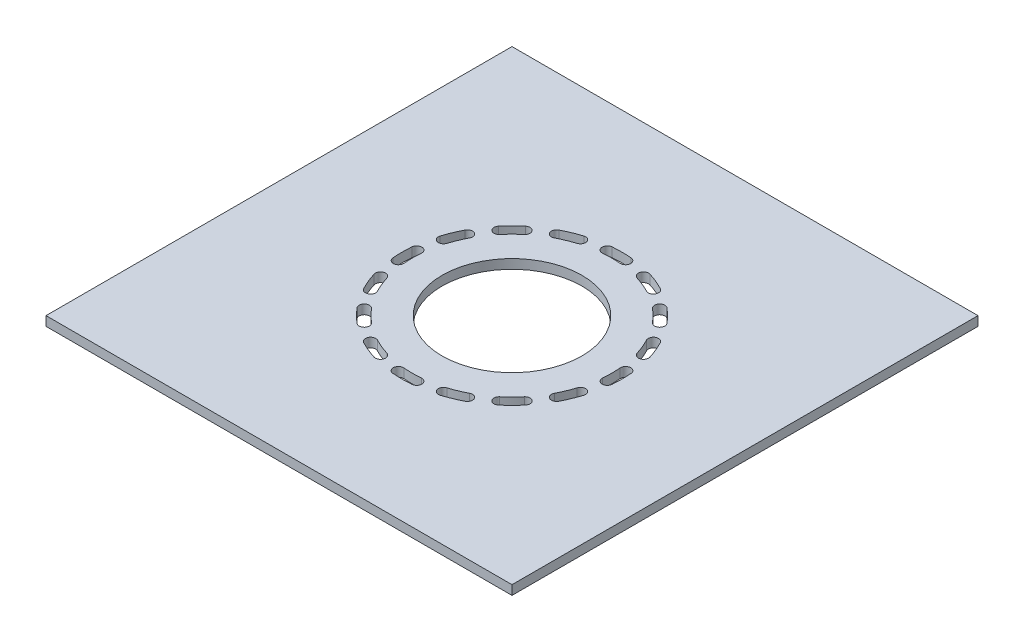
SolidWorks part; units mm, degrees
ref_plane "前视基准面" through (0, 0, 0) normal (0, 0, 1) x (1, 0, 0)
ref_plane "上视基准面" through (0, 0, 0) normal (0, 1, 0) x (1, 0, 0)
ref_plane "右视基准面" through (0, 0, 0) normal (1, 0, 0) x (0, 0, -1)
sketch "草图1" plane through (0, 0, 0) normal (0, 1, 0) x (1, 0, 0)
  line L0 (15.1321, 15.1321) -> (16.6877, 16.6877) construction
  line L1 (-50, -50) -> (50, -50)
  line L2 (-50, -50) -> (-50, 50)
  line L3 (-50, 50) -> (50, 50)
  line L4 (50, -50) -> (50, 50)
  line L5 (-50, -50) -> (50, 50) construction
  line L6 (-50, 50) -> (50, -50) construction
  line L7 (15.1698, 18.0786) -> (0, 0) construction
  circle A0 centre (0, 0) radius 15
  circle A1 centre (0, 0) radius 22.5 construction
  arc A2 (16.3934, 13.7557) -> (13.7557, 16.3934) centre (0, 0) ccw
  arc A3 (18.0786, 15.1698) -> (15.1698, 18.0786) centre (0, 0) ccw
  arc A4 (15.1698, 18.0786) -> (13.7557, 16.3934) centre (14.4627, 17.236) ccw
  arc A5 (18.0786, 15.1698) -> (16.3934, 13.7557) centre (17.236, 14.4627) cw
  arc A6 (20.9335, 10.8973) -> (18.982, 9.8814) centre (19.9577, 10.3893) ccw
  arc A7 (22.5077, 7.0967) -> (20.9335, 10.8973) centre (0, 0) ccw
  arc A8 (20.4095, 6.4351) -> (18.982, 9.8814) centre (0, 0) ccw
  arc A9 (22.5077, 7.0967) -> (20.4095, 6.4351) centre (21.4586, 6.7659) cw
  arc A10 (23.5102, 2.0569) -> (21.3186, 1.8651) centre (22.4144, 1.961) ccw
  arc A11 (23.5102, -2.0569) -> (23.5102, 2.0569) centre (0, 0) ccw
  arc A12 (21.3186, -1.8651) -> (21.3186, 1.8651) centre (0, 0) ccw
  arc A13 (23.5102, -2.0569) -> (21.3186, -1.8651) centre (22.4144, -1.961) cw
  arc A14 (22.5077, -7.0967) -> (20.4095, -6.4351) centre (21.4586, -6.7659) ccw
  arc A15 (20.9335, -10.8973) -> (22.5077, -7.0967) centre (0, 0) ccw
  arc A16 (18.982, -9.8814) -> (20.4095, -6.4351) centre (0, 0) ccw
  arc A17 (20.9335, -10.8973) -> (18.982, -9.8814) centre (19.9577, -10.3893) cw
  arc A18 (18.0786, -15.1698) -> (16.3934, -13.7557) centre (17.236, -14.4627) ccw
  arc A19 (15.1698, -18.0786) -> (18.0786, -15.1698) centre (0, 0) ccw
  arc A20 (13.7557, -16.3934) -> (16.3934, -13.7557) centre (0, 0) ccw
  arc A21 (15.1698, -18.0786) -> (13.7557, -16.3934) centre (14.4627, -17.236) cw
  arc A22 (10.8973, -20.9335) -> (9.8814, -18.982) centre (10.3893, -19.9577) ccw
  arc A23 (7.0967, -22.5077) -> (10.8973, -20.9335) centre (0, 0) ccw
  arc A24 (6.4351, -20.4095) -> (9.8814, -18.982) centre (0, 0) ccw
  arc A25 (7.0967, -22.5077) -> (6.4351, -20.4095) centre (6.7659, -21.4586) cw
  arc A26 (2.0569, -23.5102) -> (1.8651, -21.3186) centre (1.961, -22.4144) ccw
  arc A27 (-2.0569, -23.5102) -> (2.0569, -23.5102) centre (0, 0) ccw
  arc A28 (-1.8651, -21.3186) -> (1.8651, -21.3186) centre (0, 0) ccw
  arc A29 (-2.0569, -23.5102) -> (-1.8651, -21.3186) centre (-1.961, -22.4144) cw
  arc A30 (-7.0967, -22.5077) -> (-6.4351, -20.4095) centre (-6.7659, -21.4586) ccw
  arc A31 (-10.8973, -20.9335) -> (-7.0967, -22.5077) centre (0, 0) ccw
  arc A32 (-9.8814, -18.982) -> (-6.4351, -20.4095) centre (0, 0) ccw
  arc A33 (-10.8973, -20.9335) -> (-9.8814, -18.982) centre (-10.3893, -19.9577) cw
  arc A34 (-15.1698, -18.0786) -> (-13.7557, -16.3934) centre (-14.4627, -17.236) ccw
  arc A35 (-18.0786, -15.1698) -> (-15.1698, -18.0786) centre (0, 0) ccw
  arc A36 (-16.3934, -13.7557) -> (-13.7557, -16.3934) centre (0, 0) ccw
  arc A37 (-18.0786, -15.1698) -> (-16.3934, -13.7557) centre (-17.236, -14.4627) cw
  arc A38 (-20.9335, -10.8973) -> (-18.982, -9.8814) centre (-19.9577, -10.3893) ccw
  arc A39 (-22.5077, -7.0967) -> (-20.9335, -10.8973) centre (0, 0) ccw
  arc A40 (-20.4095, -6.4351) -> (-18.982, -9.8814) centre (0, 0) ccw
  arc A41 (-22.5077, -7.0967) -> (-20.4095, -6.4351) centre (-21.4586, -6.7659) cw
  arc A42 (-23.5102, -2.0569) -> (-21.3186, -1.8651) centre (-22.4144, -1.961) ccw
  arc A43 (-23.5102, 2.0569) -> (-23.5102, -2.0569) centre (0, 0) ccw
  arc A44 (-21.3186, 1.8651) -> (-21.3186, -1.8651) centre (0, 0) ccw
  arc A45 (-23.5102, 2.0569) -> (-21.3186, 1.8651) centre (-22.4144, 1.961) cw
  arc A46 (-22.5077, 7.0967) -> (-20.4095, 6.4351) centre (-21.4586, 6.7659) ccw
  arc A47 (-20.9335, 10.8973) -> (-22.5077, 7.0967) centre (0, 0) ccw
  arc A48 (-18.982, 9.8814) -> (-20.4095, 6.4351) centre (0, 0) ccw
  arc A49 (-20.9335, 10.8973) -> (-18.982, 9.8814) centre (-19.9577, 10.3893) cw
  arc A50 (-18.0786, 15.1698) -> (-16.3934, 13.7557) centre (-17.236, 14.4627) ccw
  arc A51 (-15.1698, 18.0786) -> (-18.0786, 15.1698) centre (0, 0) ccw
  arc A52 (-13.7557, 16.3934) -> (-16.3934, 13.7557) centre (0, 0) ccw
  arc A53 (-15.1698, 18.0786) -> (-13.7557, 16.3934) centre (-14.4627, 17.236) cw
  arc A54 (-10.8973, 20.9335) -> (-9.8814, 18.982) centre (-10.3893, 19.9577) ccw
  arc A55 (-7.0967, 22.5077) -> (-10.8973, 20.9335) centre (0, 0) ccw
  arc A56 (-6.4351, 20.4095) -> (-9.8814, 18.982) centre (0, 0) ccw
  arc A57 (-7.0967, 22.5077) -> (-6.4351, 20.4095) centre (-6.7659, 21.4586) cw
  arc A58 (-2.0569, 23.5102) -> (-1.8651, 21.3186) centre (-1.961, 22.4144) ccw
  arc A59 (2.0569, 23.5102) -> (-2.0569, 23.5102) centre (0, 0) ccw
  arc A60 (1.8651, 21.3186) -> (-1.8651, 21.3186) centre (0, 0) ccw
  arc A61 (2.0569, 23.5102) -> (1.8651, 21.3186) centre (1.961, 22.4144) cw
  arc A62 (7.0967, 22.5077) -> (6.4351, 20.4095) centre (6.7659, 21.4586) ccw
  arc A63 (10.8973, 20.9335) -> (7.0967, 22.5077) centre (0, 0) ccw
  arc A64 (9.8814, 18.982) -> (6.4351, 20.4095) centre (0, 0) ccw
  arc A65 (10.8973, 20.9335) -> (9.8814, 18.982) centre (10.3893, 19.9577) cw
  point P0 (0, 0)
  point P18 (15.9099, 15.9099)
  point P111 (0, 0)
  dimension "D3" = 30
  dimension "D4" = 45
  dimension "D5" = 2.2
  dimension "D1" = 100
  dimension "D2" = 100
  dimension "D6" = 5
  dimension "D7" = 16
extrude "凸台-拉伸1" add sketch "草图1" along normal blind 2
